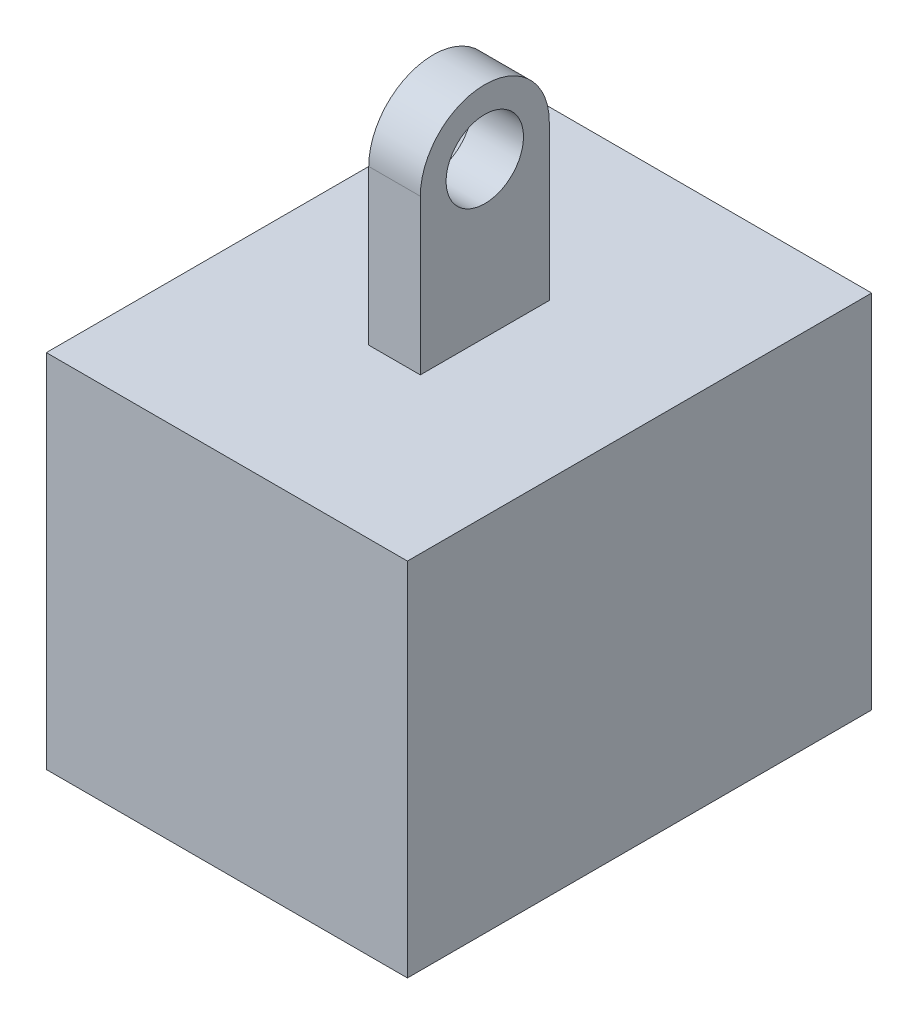
SolidWorks part; units mm, degrees
ref_plane "Plan de face" through (0, 0, 0) normal (0, 0, 1) x (1, 0, 0)
ref_plane "Plan de dessus" through (0, 0, 0) normal (0, 1, 0) x (1, 0, 0)
ref_plane "Plan de droite" through (0, 0, 0) normal (1, 0, 0) x (0, 0, -1)
sketch "Esquisse1" plane through (0, 0, 0) normal (0, 0, 1) x (1, 0, 0)
  line L1 (-35, 35) -> (35, 35)
  line L2 (-35, 35) -> (-35, -35)
  line L3 (-35, -35) -> (35, -35)
  line L4 (35, 35) -> (35, -35)
  line L5 (-35, 35) -> (35, -35) construction
  line L6 (-35, -35) -> (35, 35) construction
  point P0 (0, 0)
  dimension "D1" = 70
  dimension "D2" = 70
extrude "Boss.-Extru.1" add sketch "Esquisse1" along normal blind 90
sketch "Esquisse2" plane through (0, 0, 0) normal (1, 0, 0) x (0, 0, -1)
  line L0 (-45, 65) -> (-45, -35) construction
  line L1 (-90, -35) -> (0, -35) construction
  line L2 (-57.5, 35) -> (-57.5, 65)
  line L3 (-90, 35) -> (0, 35) construction
  line L4 (-32.5, 35) -> (-32.5, 65)
  line L5 (-57.5, 35) -> (-32.5, 35)
  arc A0 (-57.5, 65) -> (-32.5, 65) centre (-45, 65) cw
  circle A1 centre (-45, 65) radius 7.5
  point P12 (-57.5, 77.0763)
  point P13 (-45, 58.6675)
  point P14 (-45, 61.0554)
  dimension "D2" = 15
  dimension "D1" = 12.5
  dimension "D3" = 30
extrude "Boss.-Extru.2" add sketch "Esquisse2" along normal blind 5 and the other way blind 5
